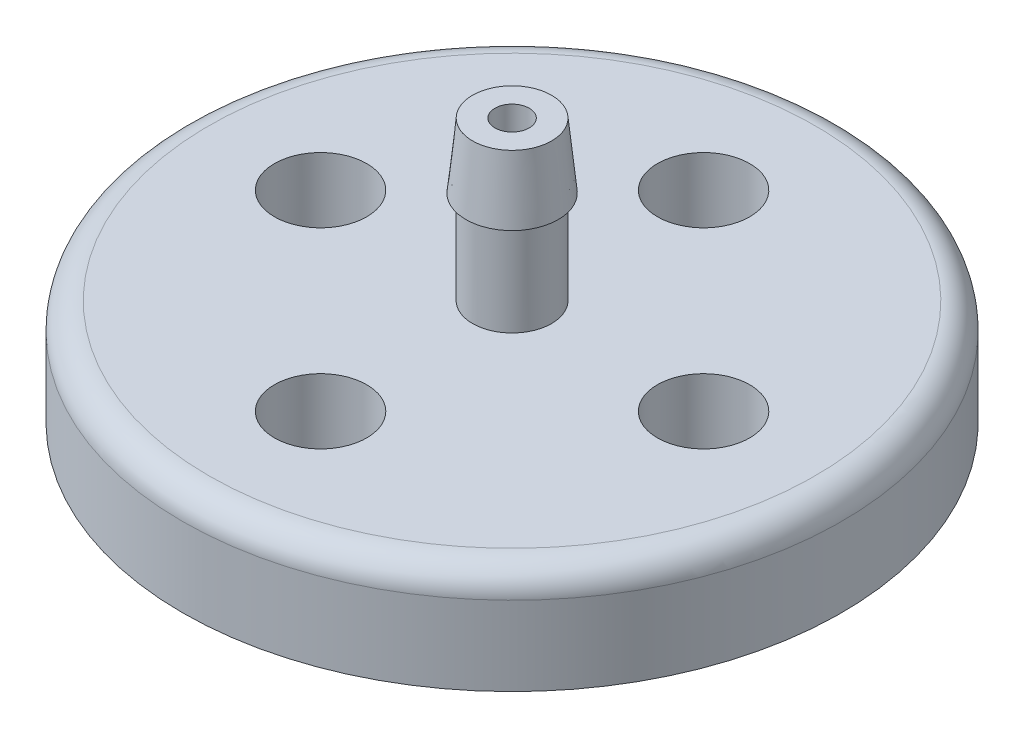
SolidWorks part; units mm, degrees
ref_plane "Front Plane" through (0, 0, 0) normal (0, 0, 1) x (1, 0, 0)
ref_plane "Top Plane" through (0, 0, 0) normal (0, 1, 0) x (1, 0, 0)
ref_plane "Right Plane" through (0, 0, 0) normal (1, 0, 0) x (0, 0, -1)
sketch "Sketch1" plane through (0, 0, 0) normal (0, 1, 0) x (1, 0, 0)
  circle A0 centre (0, 0) radius 12.5
  dimension "D1" = 25
extrude "Boss-Extrude1" add sketch "Sketch1" along normal blind 4
sketch "Sketch2" plane through (0, 4, 0) normal (0, 1, 0) x (1, 0, 0)
  circle A0 centre (0, 0) radius 1.5
  dimension "D1" = 3
extrude "Boss-Extrude2" add sketch "Sketch2" along normal blind 6
fillet "Fillet1" radius 1 1 edges at (0, 4, 12.5)
sketch "Sketch5" plane through (0, 0, 0) normal (0, 0, 1) x (1, 0, 0)
  line L0 (0, 7.54) -> (0, 10)
  line L1 (0, 10) -> (1.5, 10)
  line L2 (1.5, 10) -> (1.75, 7.54)
  line L3 (1.75, 7.54) -> (0, 7.54)
  line L4 (1.5, 10) -> (-1.5, 10) construction
  point P3 (0.75, 10)
  dimension "D1" = 2.46
  dimension "D2" = 0
  dimension "D3" = 1.5
  dimension "D4" = 1.75
revolve "Revolve1" add sketch "Sketch5" angle 360 about L0
sketch "Sketch6" plane through (0, 0, 0) normal (0, -1, 0) x (1, 0, 0)
  circle A0 centre (0, 0) radius 0.65
  dimension "D1" = 1.3
extrude "Cut-Extrude1" cut sketch "Sketch6" against normal up to next
sketch "Sketch7" plane through (0, 0, 0) normal (0, -1, 0) x (1, 0, 0)
  line L0 (0, 0) -> (-12.5, 0) construction
  circle A0 centre (0, 0) radius 12.5 construction
  circle A1 centre (-7.2632, 0) radius 1.75
  dimension "D1" = 3.5
  dimension "D2" = 7.2632
extrude "Cut-Extrude2" cut sketch "Sketch7" against normal up to next
pattern_circular "CirPattern1" count 4 over 360 about axis through (0, 0, 0) along (0, 1, 0) of "Cut-Extrude2"
